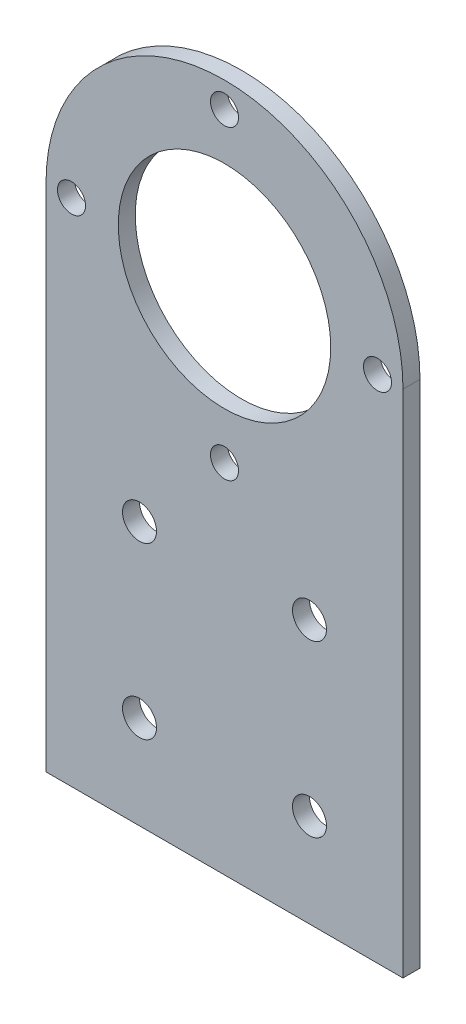
SolidWorks part; units mm, degrees
ref_plane "Piano frontale" through (0, 0, 0) normal (0, 0, 1) x (1, 0, 0)
ref_plane "Piano superiore" through (0, 0, 0) normal (0, 1, 0) x (1, 0, 0)
ref_plane "Piano destro" through (0, 0, 0) normal (1, 0, 0) x (0, 0, -1)
sketch "Schizzo1" plane through (0, 0, 0) normal (0, 0, 1) x (1, 0, 0)
  line L1 (21, 0) -> (21, -60)
  line L2 (-21, 0) -> (-21, -60)
  line L3 (-21, -60) -> (21, -60)
  arc A0 (21, 0) -> (-21, 0) centre (0, 0) ccw
extrude "Estrusione-Estrusione1" add sketch "Schizzo1" along normal blind 2 contours L2 L3 L1 A0
sketch "Schizzo2" plane through (0, 0, 2) normal (0, 0, 1) x (1, 0, 0)
  circle A0 centre (-18, 0) radius 1.65
  circle A1 centre (18, 0) radius 1.65
  circle A3 centre (0, 18) radius 1.65
  circle A4 centre (0, -18) radius 1.65
  point P19 (0, 0)
sketch "Schizzo3" plane through (0, 0, 2) normal (0, 0, 1) x (1, 0, 0)
  circle A0 centre (0, 0) radius 12.5
extrude "Taglio-Estrusione1" cut sketch "Schizzo2" against normal blind 2
extrude "Taglio-Estrusione2" cut sketch "Schizzo3" against normal blind 2
sketch "Schizzo4" plane through (0, 0, 2) normal (0, 0, 1) x (1, 0, 0)
  circle A0 centre (-10, -29) radius 2
  circle A1 centre (10, -29) radius 2
  circle A2 centre (10, -49) radius 2
  circle A3 centre (-10, -49) radius 2
extrude "Taglio-Estrusione3" cut sketch "Schizzo4" against normal blind 2
